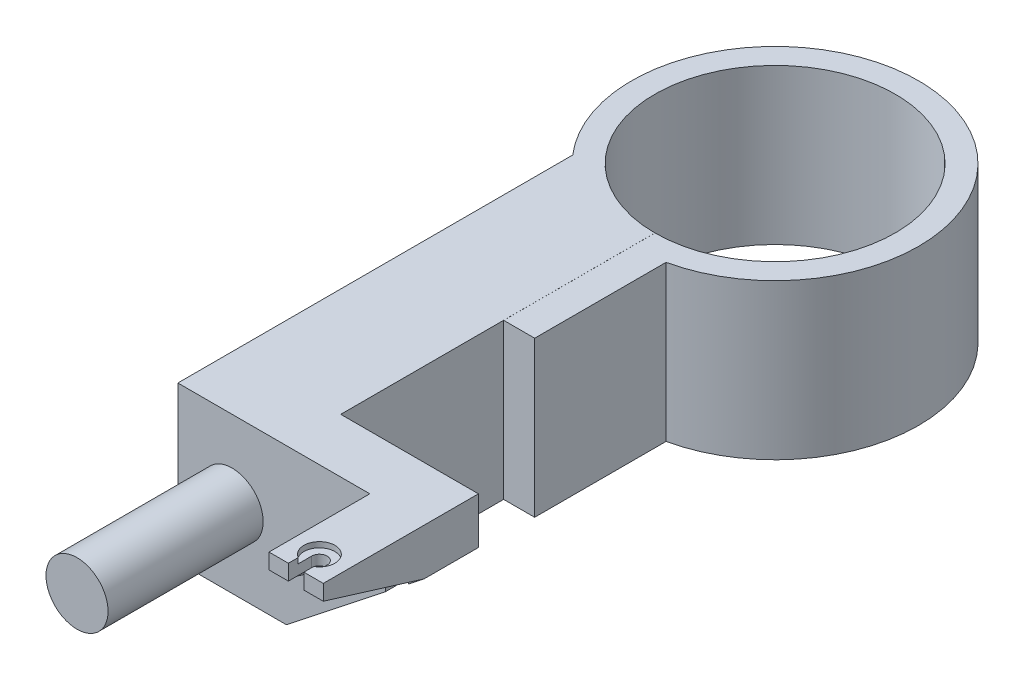
SolidWorks part; units mm, degrees
ref_plane "Front Plane" through (0, 0, 0) normal (0, 0, 1) x (1, 0, 0)
ref_plane "Top Plane" through (0, 0, 0) normal (0, 1, 0) x (1, 0, 0)
ref_plane "Right Plane" through (0, 0, 0) normal (1, 0, 0) x (0, 0, -1)
sketch "Sketch1" plane through (0, 0, 0) normal (0, 1, 0) x (1, 0, 0)
  line L0 (0, -15.5) -> (0, -63)
  line L1 (0, 18.5) -> (0, 15.5)
  line L2 (-14, -12.0934) -> (-14, -63)
  line L3 (-11, -60) -> (-11, -14.8745)
  line L4 (-3, -60) -> (-3, -18.2551)
  line L6 (-14, -63) -> (0, -63)
  line L8 (-11, -60) -> (-3, -60)
  arc A0 (0, 15.5) -> (0, -15.5) centre (0, 0) ccw
  arc A1 (0, 18.5) -> (-14, -12.0934) centre (0, 0) ccw
  arc A2 (-11, -14.8745) -> (-3, -18.2551) centre (0, 0) ccw
  dimension "D3" = 15.5
  dimension "D4" = 3
  dimension "D1" = 3
  dimension "D2" = 3
  dimension "D5" = 8
  dimension "D6" = 63
  dimension "D7" = 3
extrude "Boss-Extrude1" add sketch "Sketch1" along normal blind 20 contours A0 L0 L6 L4 A2 L3 L2 A1 L1
sketch "Sketch2" plane through (0, 0, 63) normal (0, 0, 1) x (1, 0, 0)
  line L0 (0, 10) -> (-14, 10) construction
  line L1 (0, 20) -> (0, 0) construction
  line L2 (-14, 20) -> (-14, 0) construction
  line L3 (-7, 20) -> (-7, 0) construction
  line L4 (-14, 20) -> (0, 20) construction
  line L5 (-14, 0) -> (0, 0) construction
  circle A0 centre (-7, 10) radius 4
  dimension "D1" = 8
extrude "Boss-Extrude2" add sketch "Sketch2" along normal blind 20
sketch "Sketch3" plane through (0, 20, 0) normal (0, 1, 0) x (1, 0, 0)
  line L0 (0, -63) -> (10.7494, -63)
  line L1 (10.7494, -63) -> (10.7494, -76)
  line L2 (10.7494, -76) -> (13.2494, -76)
  line L3 (17.7494, -76) -> (17.7494, -56)
  line L4 (17.7494, -56) -> (0, -56)
  line L5 (0, -63) -> (0, -15.5) construction
  line L6 (0, -56) -> (0, -63)
  line L7 (2, -58) -> (15.7494, -58)
  line L8 (15.7494, -58) -> (15.7494, -69)
  line L9 (2, -58) -> (2, -61)
  line L10 (2, -61) -> (12.7494, -61)
  line L11 (12.7494, -61) -> (12.7494, -69)
  line L12 (14.2494, -76) -> (14.2494, -73) construction
  line L13 (15.2494, -73) -> (15.2494, -76)
  line L14 (13.2494, -73) -> (13.2494, -76)
  line L15 (15.2494, -76) -> (17.7494, -76)
  line L16 (12.7494, -69) -> (15.7494, -69)
  line L17 (-3, -73) -> (14.2494, -73) construction
  line L18 (-3, -83) -> (-3, -63) construction
  line L19 (10.7494, -69.5) -> (17.7494, -69.5) construction
  line L20 (14.2494, -69.5) -> (14.2494, -73) construction
  arc A0 (15.2494, -73) -> (13.2494, -73) centre (14.2494, -73) ccw
  dimension "D1" = 2
  dimension "D2" = 3
  dimension "D3" = 2
  dimension "D4" = 2
  dimension "D5" = 2
  dimension "D6" = 2
  dimension "D7" = 2
  dimension "D8" = 7
  dimension "D9" = 7
  dimension "D13" = 7
extrude "Boss-Extrude3" add sketch "Sketch3" against normal blind 2
sketch "Sketch4" plane through (0, 18, 0) normal (0, -1, 0) x (1, 0, 0)
  line L0 (15.7494, 58) -> (2, 58) construction
  line L1 (15.7494, 69) -> (15.7494, 58) construction
  line L2 (12.7494, 69) -> (15.7494, 69) construction
  line L3 (12.7494, 61) -> (12.7494, 69) construction
  line L4 (2, 61) -> (12.7494, 61) construction
  line L5 (2, 58) -> (2, 61) construction
  line L6 (15.7494, 58) -> (2, 58)
  line L7 (15.7494, 69) -> (15.7494, 58)
  line L8 (12.7494, 69) -> (15.7494, 69)
  line L9 (0, 63) -> (0, 56)
  line L10 (0, 56) -> (17.7494, 56)
  line L11 (17.7494, 56) -> (17.7494, 76)
  line L12 (17.7494, 76) -> (15.2494, 76)
  line L13 (15.2494, 76) -> (15.2494, 73)
  line L14 (13.2494, 73) -> (13.2494, 76)
  line L15 (13.2494, 76) -> (10.7494, 76)
  line L16 (10.7494, 76) -> (10.7494, 63)
  line L17 (10.7494, 63) -> (0, 63)
  line L18 (0, 63) -> (0, 56)
  line L19 (0, 56) -> (17.7494, 56)
  line L20 (10.7494, 63) -> (10.7494, 66)
  line L21 (10.7494, 63) -> (10.7494, 76) construction
  line L22 (17.7494, 66) -> (17.7494, 76)
  line L23 (17.7494, 56) -> (17.7494, 66)
  line L24 (17.7494, 76) -> (17.7494, 56) construction
  line L25 (17.7494, 76) -> (15.7494, 76)
  line L26 (10.7494, 63) -> (0, 63)
  line L27 (12.7494, 61) -> (12.7494, 69)
  line L28 (2, 61) -> (12.7494, 61)
  line L29 (2, 58) -> (2, 61)
  line L30 (15.2494, 76) -> (17.7494, 76) construction
  line L31 (15.7494, 76) -> (15.7494, 69)
  line L32 (10.7494, 66) -> (10.7494, 76)
  line L33 (10.7494, 76) -> (12.7494, 76)
  line L34 (10.7494, 76) -> (13.2494, 76) construction
  line L35 (12.7494, 76) -> (12.7494, 69)
  arc A1 (13.2494, 73) -> (15.2494, 73) centre (14.2494, 73) ccw
  dimension "D1" = 0
extrude "Boss-Extrude4" add sketch "Sketch4" along normal up to surface (18 mm away) up to face at (-8.887, 0, 19.1831)
sketch "Sketch5" plane through (0, 0, 56) normal (0, 0, -1) x (-1, 0, 0)
  line L0 (0, 0) -> (-17.7494, 14)
  line L1 (-17.7494, 0) -> (-17.7494, 20) construction
  line L2 (-17.7494, 14) -> (-17.7494, -1.5545)
  line L3 (-17.7494, -1.5545) -> (0, -1.5545)
  line L4 (0, -1.5545) -> (0, 0)
  line L5 (-17.7494, 20) -> (0, 20) construction
  dimension "D1" = 6
extrude "Cut-Extrude1" cut sketch "Sketch5" against normal blind 22
sketch "Sketch7" plane through (0, 20, 0) normal (0, 1, 0) x (1, 0, 0)
  line L0 (2, -61) -> (12.7494, -61) construction
  line L1 (2, -58) -> (2, -61) construction
  line L2 (15.7494, -58) -> (2, -58) construction
  line L3 (15.7494, -69) -> (15.7494, -58) construction
  line L4 (12.7494, -69) -> (15.7494, -69) construction
  line L5 (12.7494, -61) -> (12.7494, -69) construction
  line L6 (2, -61) -> (12.7494, -61)
  line L7 (2, -58) -> (2, -61)
  line L8 (15.7494, -58) -> (2, -58)
  line L9 (15.7494, -69) -> (15.7494, -58)
  line L10 (12.7494, -69) -> (15.7494, -69)
  line L11 (12.7494, -61) -> (12.7494, -69)
extrude "Boss-Extrude5" add sketch "Sketch7" against normal up to surface (2 mm away)
sketch "Sketch8" plane through (0, 20, 0) normal (0, 1, 0) x (1, 0, 0)
  circle A0 centre (14.2494, -73) radius 2
  dimension "D1" = 4
extrude "Cut-Extrude3" cut sketch "Sketch8" against normal blind 0.7
sketch "Sketch6" plane through (17.7494, 0, 0) normal (1, 0, 0) x (0, 0, -1)
  line L0 (-76, 14) -> (-56, 14) construction
  line L2 (-63, 14) -> (-82.697, 14)
  line L3 (-82.697, 14) -> (-82.697, 0.4151)
  line L4 (-82.697, 0.4151) -> (-63, 0.4151)
  line L5 (-63, 14) -> (-63, 6) construction
  line L6 (-63, 0.4151) -> (-63, 14)
extrude "Cut-Extrude2" cut sketch "Sketch6" against normal up to surface (7 mm away) up to face at (10.7494, 14.2393, 69.5)
sketch "Sketch10" plane through (17.7494, 0, 0) normal (1, 0, 0) x (0, 0, -1)
  line L0 (-63, 14) -> (-76, 18)
  line L1 (-76, 14) -> (-76, 20) construction
  line L2 (-76, 18) -> (-76, 12.2169)
  line L3 (-76, 12.2169) -> (-63, 12.2169)
  line L4 (-63, 12.2169) -> (-63, 14)
extrude "Cut-Extrude4" cut sketch "Sketch10" against normal up to surface (7 mm away) up to face at (10.7494, 17, 69.5)
sketch "Sketch11" plane through (0, 20, 0) normal (0, 1, 0) x (1, 0, 0)
  line L0 (-11, -14.8745) -> (-11, -60) construction
  line L1 (-3, -60) -> (-3, -18.2551) construction
  line L2 (-11, -60) -> (-3, -60) construction
  line L3 (-11, -14.8745) -> (-11, -60)
  line L4 (-3, -60) -> (-3, -18.2551)
  line L5 (-11, -60) -> (-3, -60)
  arc A0 (-11, -14.8745) -> (-3, -18.2551) centre (0, 0) ccw construction
  arc A1 (-11, -14.8745) -> (-3, -18.2551) centre (0, 0) ccw
extrude "Boss-Extrude6" add sketch "Sketch11" against normal blind 2 contours L3 L5 L4 A1
sketch "Sketch12" plane through (0, 0, 0) normal (0, -1, 0) x (1, 0, 0)
  line L0 (-3, 60) -> (-3, 18.2551) construction
  line L1 (-11, 60) -> (-3, 60) construction
  line L2 (-11, 14.8745) -> (-11, 60) construction
  line L3 (-3, 60) -> (-3, 18.2551)
  line L4 (-11, 60) -> (-3, 60)
  line L5 (-11, 14.8745) -> (-11, 60)
  arc A0 (-3, 18.2551) -> (-11, 14.8745) centre (0, 0) ccw construction
  arc A1 (-3, 18.2551) -> (-11, 14.8745) centre (0, 0) ccw
extrude "Boss-Extrude7" add sketch "Sketch12" against normal blind 2
sketch "Sketch13" plane through (0, 20, 0) normal (0, 1, 0) x (1, 0, 0)
  line L0 (0, 15.5) -> (0, 18.5)
  line L1 (0.01, -35) -> (4, -35)
  line L2 (0, -56) -> (0, -15.5) construction
  line L3 (4, -35) -> (4, -18.0624)
  line L4 (0.01, -35) -> (0.01, -15.5)
  arc A0 (0.01, -15.5) -> (0, 15.5) centre (0, 0) ccw
  arc A1 (4, -18.0624) -> (0, 18.5) centre (0, 0) ccw
  dimension "D1" = 4
  dimension "D2" = 0.01
  dimension "D3" = 35
extrude "Boss-Extrude8" add sketch "Sketch13" against normal up to surface (20 mm away) contours A0 L0 A1 L3 L1 L4 up to face at (-7.6175, 0, 24.4427)
